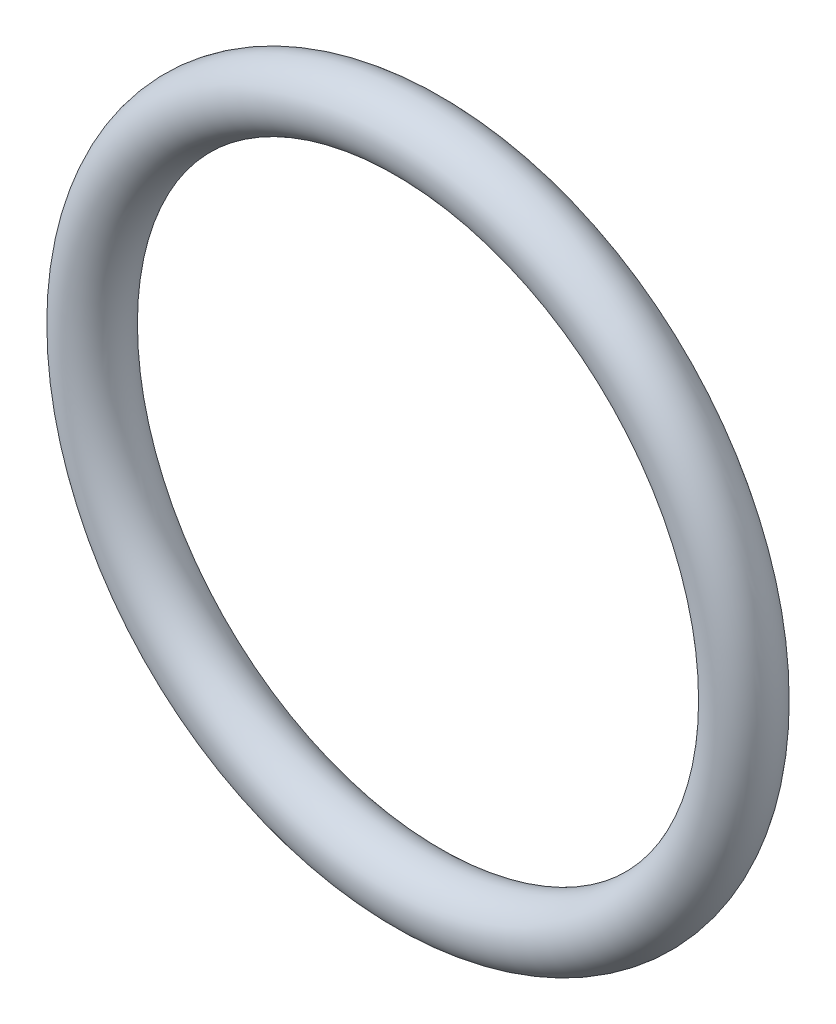
SolidWorks part; units mm, degrees
material "Silicon Rubber"
ref_plane "Front Plane" through (0, 0, 0) normal (0, 0, 1) x (1, 0, 0)
ref_plane "Top Plane" through (0, 0, 0) normal (0, 1, 0) x (1, 0, 0)
ref_plane "Right Plane" through (0, 0, 0) normal (1, 0, 0) x (0, 0, -1)
sketch "Sketch2" plane through (0, 0, 0) normal (0, 1, 0) x (1, 0, 0)
  line L0 (0, 9.8707) -> (0, -9.9883) construction
  line L1 (0, 0) -> (6.985, 0) construction
  line L2 (6.985, 0) -> (7.747, 0) construction
  circle A0 centre (7.747, 0) radius 0.762
  dimension "D1" = 6.985
  dimension "D2" = 0.762
revolve "Revolve1" add sketch "Sketch2" angle 360 about L0
